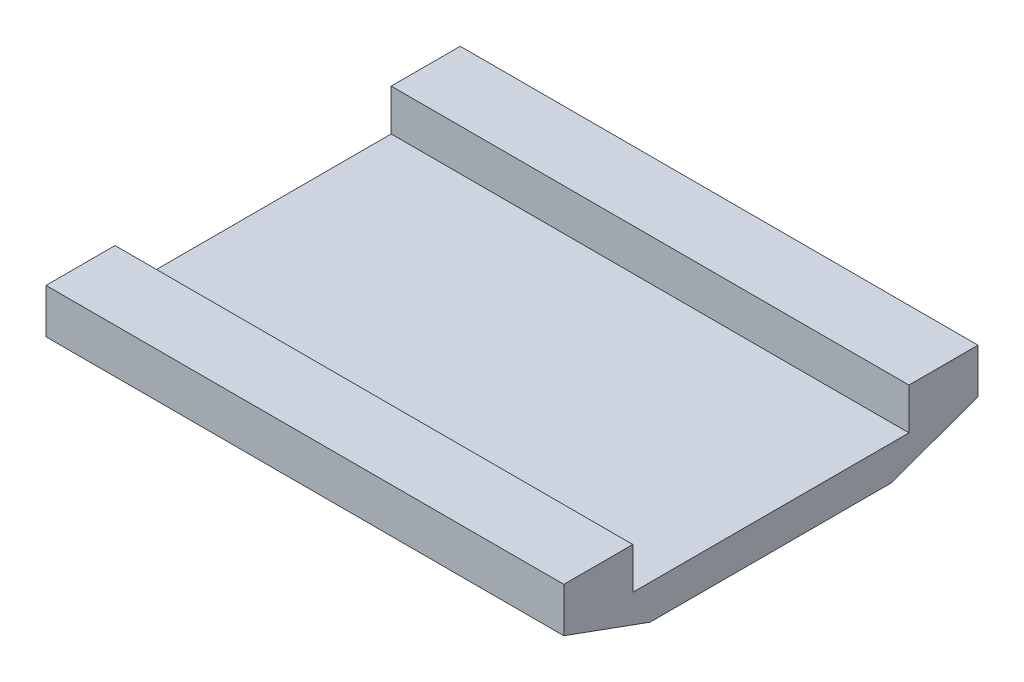
SolidWorks part; units mm, degrees
ref_plane "Front Plane" through (0, 0, 0) normal (0, 0, 1) x (1, 0, 0)
ref_plane "Top Plane" through (0, 0, 0) normal (0, 1, 0) x (1, 0, 0)
ref_plane "Right Plane" through (0, 0, 0) normal (1, 0, 0) x (0, 0, -1)
sketch "Sketch1" plane through (0, 0, 0) normal (0, 1, 0) x (1, 0, 0)
  line L1 (-16.5365, 10.1887) -> (21.5635, 10.1887)
  line L2 (-16.5365, 10.1887) -> (-16.5365, -20.2913)
  line L3 (-16.5365, -20.2913) -> (21.5635, -20.2913)
  line L4 (21.5635, 10.1887) -> (21.5635, -20.2913)
  line L5 (21.5635, -15.2113) -> (-16.5365, -15.2113)
  line L6 (21.5635, -15.2113) -> (21.5635, 5.1087)
  line L7 (21.5635, 5.1087) -> (-16.5365, 5.1087)
  line L8 (-16.5365, -15.2113) -> (-16.5365, 5.1087)
  dimension "D1" = 38.1
  dimension "D2" = 30.48
  dimension "D3" = 20.32
  dimension "D4" = 5.08
extrude "Boss-Extrude1" add sketch "Sketch1" along normal blind 2.54 contours L6 L5 L8 L7
sketch "Sketch2" plane through (0, 0, 0) normal (0, 1, 0) x (1, 0, 0)
  line L1 (-16.5365, 10.1887) -> (21.5635, 10.1887)
  line L2 (-16.5365, 10.1887) -> (-16.5365, 5.1087)
  line L3 (-16.5365, 5.1087) -> (21.5635, 5.1087)
  line L4 (21.5635, 10.1887) -> (21.5635, 5.1087)
  line L5 (21.5635, -15.2113) -> (-16.5365, -15.2113)
  line L6 (21.5635, -15.2113) -> (21.5635, -20.2913)
  line L7 (21.5635, -20.2913) -> (-16.5365, -20.2913)
  line L8 (-16.5365, -15.2113) -> (-16.5365, -20.2913)
extrude "Boss-Extrude2" add sketch "Sketch2" along normal blind 5.588
chamfer "Chamfer1" distance 6.35 angle 20 2 edges at (2.5135, 0, -10.1887) (2.5135, 0, 20.2913)
